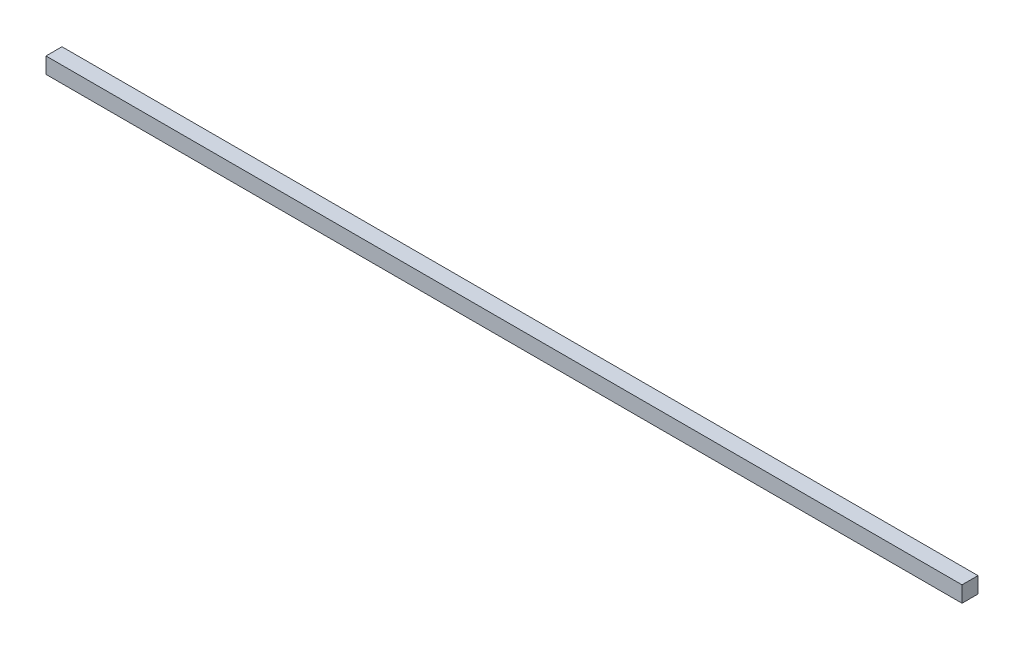
SolidWorks part; units mm, degrees
ref_plane "Front Plane" through (0, 0, 0) normal (0, 0, 1) x (1, 0, 0)
ref_plane "Top Plane" through (0, 0, 0) normal (0, 1, 0) x (1, 0, 0)
ref_plane "Right Plane" through (0, 0, 0) normal (1, 0, 0) x (0, 0, -1)
sketch "Sketch1" plane through (0, 0, 0) normal (1, 0, 0) x (0, 0, -1)
  line L1 (4.6429, -20.8929) -> (24.6429, -20.8929)
  line L2 (4.6429, -20.8929) -> (4.6429, -40.8929)
  line L3 (4.6429, -40.8929) -> (24.6429, -40.8929)
  line L4 (24.6429, -20.8929) -> (24.6429, -40.8929)
  dimension "D1" = 20
  dimension "D2" = 20
extrude "Boss-Extrude1" add sketch "Sketch1" along normal mid plane 1146.8
